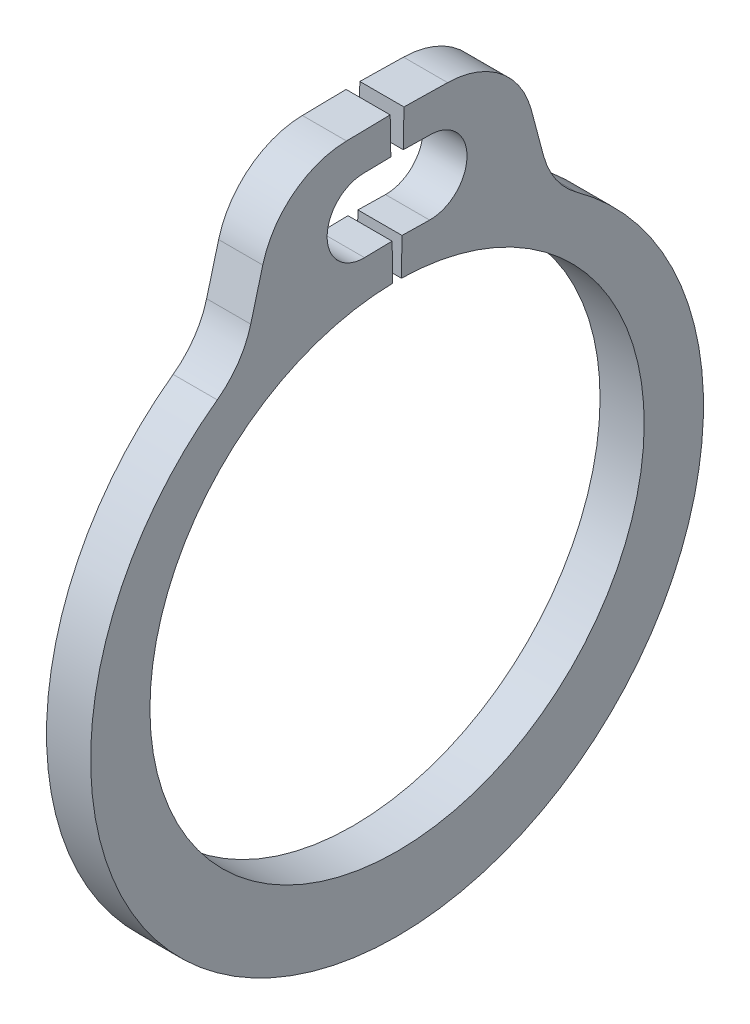
SolidWorks part; units mm, degrees
material "Cast Carbon Steel"
ref_plane "Front" through (0, 0, 0) normal (0, 0, 1) x (1, 0, 0)
ref_plane "Top" through (0, 0, 0) normal (0, 1, 0) x (1, 0, 0)
ref_plane "Right" through (0, 0, 0) normal (1, 0, 0) x (0, 0, -1)
sketch "Sketch1" plane through (0, 0, 0) normal (1, 0, 0) x (0, 0, -1)
  line L0 (0, 0) -> (0, 2.1336) construction
  line L1 (-0.0372, 2.1333) -> (-0.0594, 3.4031) construction
  line L2 (0.0594, 3.4031) -> (1.0118, 3.3865)
  line L3 (1.0118, 3.3865) -> (1.3379, 2.1591)
  line L4 (0.0372, 2.1333) -> (0.0594, 3.4031) construction
  line L5 (-0.0594, 3.4031) -> (-1.0118, 3.3865)
  line L6 (-1.0118, 3.3865) -> (-1.3379, 2.1591)
  line L7 (-1.3379, 2.1591) -> (-1.1239, 1.8136) construction
  line L8 (1.3379, 2.1591) -> (1.1239, 1.8136) construction
  line L9 (0, -2.1336) -> (0, -2.7686) construction
  line L10 (-1.0118, 3.3865) -> (-0.0372, 2.1333) construction
  line L11 (0, 2.1336) -> (0, 3.4036) construction
  line L12 (0.0428, 2.4507) -> (0.2809, 2.4466)
  line L13 (0.0539, 3.0856) -> (0.2919, 3.0815)
  line L14 (0.0428, 2.4507) -> (0.0372, 2.1333)
  line L15 (0.0539, 3.0856) -> (0.0594, 3.4031)
  line L16 (-0.0539, 3.0856) -> (-0.2919, 3.0815)
  line L17 (-0.0428, 2.4507) -> (-0.2809, 2.4466)
  line L18 (-0.0428, 2.4507) -> (-0.0372, 2.1333)
  line L19 (-0.0539, 3.0856) -> (-0.0594, 3.4031)
  line L20 (-2.1336, 0) -> (2.1336, 0) construction
  circle A0 centre (0, 0) radius 2.1336 construction
  arc A1 (-0.0372, 2.1333) -> (0.0372, 2.1333) centre (0, 0) ccw
  arc A2 (0.2809, 2.4466) -> (0.2919, 3.0815) centre (0.2864, 2.764) ccw
  circle A3 centre (0, 0) radius 3.7846 construction
  arc A4 (-0.2809, 2.4466) -> (-0.2919, 3.0815) centre (-0.2864, 2.764) cw
  arc A6 (-1.3379, 2.1591) -> (1.3379, 2.1591) centre (0, -0.1231) ccw
  point P0 (0, -2.7686)
  dimension "A" = 4.2672
  dimension "D2" = 0.9525
  dimension "L" = 7.5692
  dimension "Smin" = 0.4064
  dimension "Smax" = 0.635
  dimension "H" = 1.27
  dimension "Angle" = 1
  dimension "R" = 0.635
extrude "Extrude1" add sketch "Sketch1" along normal mid plane 0.381
fillet "Fillet1" radius 0.762 4 edges at (0, 2.1591, 1.3379) (0, 2.1591, -1.3379) (0, 3.3865, 1.0118) (0, 3.3865, -1.0118)
sketch "Sketch2" plane through (0, 0, 0) normal (0, 0, 1) x (1, 0, 0)
  line L0 (-2.1336, 0) -> (5.4864, 0)
  line L1 (5.4864, 0) -> (5.4864, -2.3812)
  line L2 (-0.2286, -2.3812) -> (-1.9748, -2.3812)
  line L3 (5.4864, -2.3812) -> (0.2286, -2.3812)
  line L4 (0.2286, -2.3812) -> (0.2286, -2.2225)
  line L5 (0.2286, -2.2225) -> (-0.2286, -2.2225)
  line L6 (-0.2286, -2.2225) -> (-0.2286, -2.3812)
  line L7 (-0.2286, -2.3812) -> (-2.1336, -2.3812) construction
  line L8 (-2.1336, -2.3812) -> (-2.1336, 0) construction
  line L9 (5.4864, 0) -> (76.391, 0) construction
  line L10 (-1.9748, -2.3812) -> (-2.1336, -2.2225)
  line L11 (-2.1336, -2.2225) -> (-2.1336, 0)
  point P10 (0, -2.2225)
  dimension "D1" = 45
  dimension "Dg" = 4.445
  dimension "Ds" = 4.7625
  dimension "W" = 0.4572
  dimension "D2" = 7.62
  dimension "D3" = 1.905
revolve "Revolve1" [suppressed] add sketch "Sketch2" angle 360 about L9
delete or keep bodies "Body-Delete1" [suppressed] type delete bodies bodies 122
equation "\"D2@Sketch2\" = \"D1@Extrude1\"*20"
equation "\"D3@Sketch2\" = \"D2@Sketch2\"/4"
equation "\"D2@Sketch1\" = \"H@Sketch1\"*.75"
equation "\"D1@Fillet1\" = \"D1@Extrude1\"*2"
